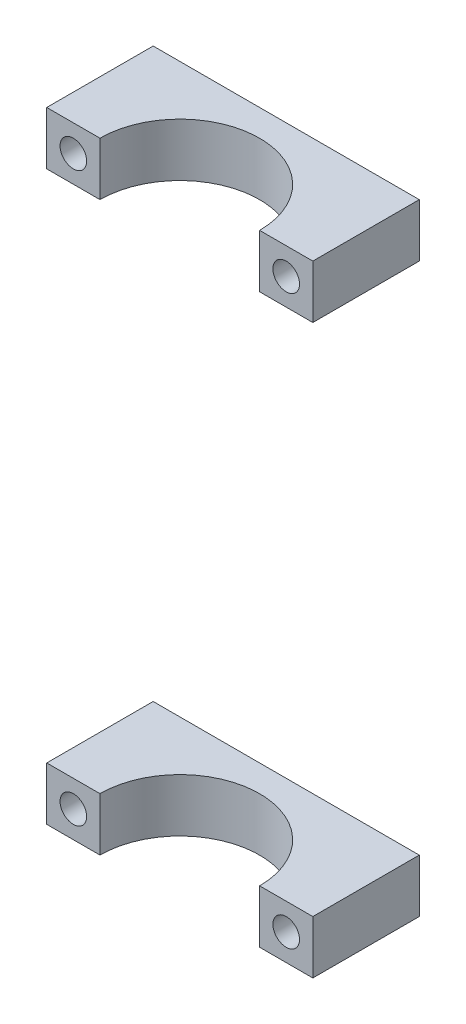
SolidWorks part; units mm, degrees
ref_plane "Front Plane" through (0, 0, 0) normal (0, 0, 1) x (1, 0, 0)
ref_plane "Top Plane" through (0, 0, 0) normal (0, 1, 0) x (1, 0, 0)
ref_plane "Right Plane" through (0, 0, 0) normal (1, 0, 0) x (0, 0, -1)
sketch "Sketch1" plane through (0, 0, 0) normal (0, 0, 1) x (1, 0, 0)
  line L1 (0, 0) -> (50, 0)
  line L2 (0, 0) -> (0, 100)
  line L3 (0, 100) -> (50, 100)
  line L4 (50, 0) -> (50, 100)
  dimension "D1" = 100
  dimension "D2" = 50
extrude "Boss-Extrude1" add sketch "Sketch1" along normal blind 30
sketch "Sketch2" plane through (0, 0, 30) normal (0, 0, 1) x (1, 0, 0)
  line L0 (50, 100) -> (0, 100) construction
  line L1 (4, 4) -> (46, 4)
  line L2 (4, 4) -> (4, 96)
  line L3 (4, 96) -> (46, 96)
  line L4 (46, 4) -> (46, 96)
  line L5 (0, 100) -> (0, 0) construction
  line L6 (50, 0) -> (50, 100) construction
  line L7 (0, 0) -> (50, 0) construction
  dimension "D1" = 4
  dimension "D2" = 4
  dimension "D3" = 4
  dimension "D4" = 4
extrude "Cut-Extrude1" cut sketch "Sketch2" against normal blind 26
sketch "Sketch3" plane through (0, 0, 0) normal (0, 0, -1) x (-1, 0, 0)
  line L0 (0, 0) -> (-50, 0) construction
  line L1 (-40, 21) -> (-10, 21)
  line L2 (-40, 21) -> (-40, 15)
  line L3 (-40, 15) -> (-10, 15)
  line L4 (-10, 21) -> (-10, 15)
  line L5 (-50, 50) -> (0, 50) construction
  line L6 (-50, 0) -> (-50, 100) construction
  line L7 (0, 100) -> (0, 0) construction
  line L8 (-40, 85) -> (-10, 85)
  line L9 (-10, 79) -> (-10, 85)
  line L10 (-40, 79) -> (-10, 79)
  line L11 (-40, 79) -> (-40, 85)
  point P6 (-25, 15)
  point P7 (-25, 0)
  dimension "D1" = 6
  dimension "D2" = 15
  dimension "D3" = 30
  dimension "D4" = 0
extrude "Boss-Extrude2" add sketch "Sketch3" along normal blind 24
sketch "Sketch4" plane through (0, 15, 0) normal (0, -1, 0) x (1, 0, 0)
  line L1 (40, -24) -> (40, 0) construction
  line L2 (40, -24) -> (10, -24) construction
  circle A0 centre (25, -12) radius 9
  dimension "D1" = 18
  dimension "D2" = 15
  dimension "D3" = 12
extrude "Cut-Extrude2" cut sketch "Sketch4" against normal through all both and the other way through all
sketch "Sketch5" plane through (0, 0, -24) normal (0, 0, -1) x (-1, 0, 0)
  line L0 (-40, 15) -> (-10, 15) construction
  line L2 (-10, 15) -> (-10, 21) construction
  line L3 (-10, 21) -> (-40, 21) construction
  line L4 (-40, 21) -> (-40, 15) construction
  line L5 (-10, 85) -> (-40, 85) construction
  line L6 (-10, 79) -> (-10, 85) construction
  line L7 (-40, 85) -> (-40, 79) construction
  line L8 (-40, 79) -> (-10, 79) construction
  circle A0 centre (-13, 18) radius 1.5
  circle A1 centre (-37, 18) radius 1.5
  circle A2 centre (-13, 82) radius 1.5
  circle A3 centre (-37, 82) radius 1.5
  dimension "D1" = 3
  dimension "D2" = 3
  dimension "D3" = 3
  dimension "D4" = 3
  dimension "D5" = 3
  dimension "D6" = 3
  dimension "D7" = 3
  dimension "D8" = 3
  dimension "D9" = 3
  dimension "D10" = 3
  dimension "D11" = 3
  dimension "D12" = 3
extrude "Cut-Extrude3" cut sketch "Sketch5" against normal through all both and the other way through all
sketch "Sketch6" plane through (0, 0, 0) normal (0, -1, 0) x (1, 0, 0)
  line L0 (50, 30) -> (50, 0) construction
  line L1 (40, -24) -> (10, -24) construction
  line L2 (0, 30) -> (50, 30)
  line L3 (0, 30) -> (0, -12)
  line L4 (0, -12) -> (50, -12)
  line L5 (50, 30) -> (50, -12)
  dimension "D1" = 0
  dimension "D2" = 12
extrude "Cut-Extrude4" cut sketch "Sketch6" against normal through all both and the other way through all
